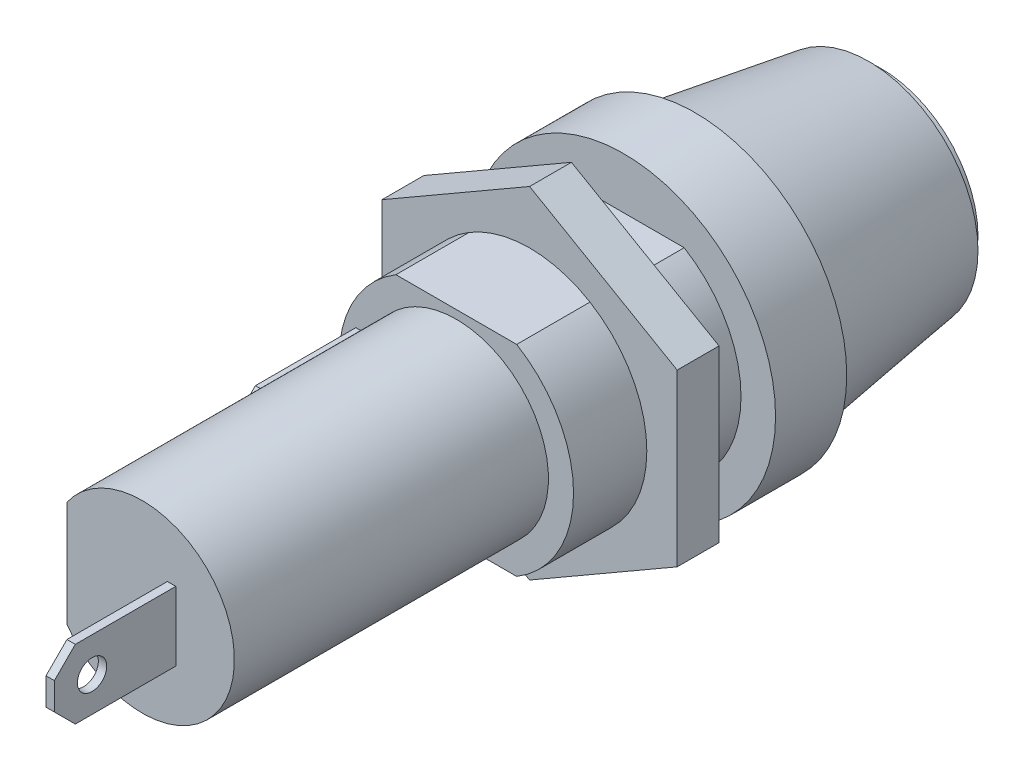
SolidWorks part; units mm, degrees
ref_plane "Front" through (0, 0, 0) normal (0, 0, 1) x (1, 0, 0)
ref_plane "Top" through (0, 0, 0) normal (0, 1, 0) x (1, 0, 0)
ref_plane "Right" through (0, 0, 0) normal (1, 0, 0) x (0, 0, -1)
sketch "Sketch1" plane through (0, 0, 0) normal (0, 0, 1) x (1, 0, 0)
  circle A0 centre (0, 0) radius 9.2075
  dimension "D1" = 18.415
extrude "Boss-Extrude1" add sketch "Sketch1" along normal blind 4.318
sketch "Sketch2" plane through (0, 0, 0) normal (1, 0, 0) x (0, 0, -1)
  line L0 (0, 0) -> (11.303, 0) construction
  line L1 (0, 0) -> (0, 8.4582)
  line L2 (0, -9.2075) -> (0, 9.2075) construction
  line L3 (0, 8.4582) -> (0.508, 8.4582)
  line L6 (10.541, 6.6294) -> (10.541, 5.8674)
  line L7 (10.541, 5.8674) -> (11.303, 5.8674)
  line L8 (11.303, 5.8674) -> (11.303, 0)
  line L9 (11.303, 0) -> (0, 0)
  line L10 (0.508, 8.4582) -> (0.6009, 8.143)
  line L11 (0.6009, 8.143) -> (10.541, 6.6294)
  dimension "D1" = 11.303
  dimension "D2" = 0.762
  dimension "D3" = 0.762
  dimension "D4" = 5.8674
  dimension "D5" = 0.508
  dimension "D6" = 8.4582
revolve "Revolve1" add sketch "Sketch2" angle 360 about L0
sketch "Sketch3" plane through (0, 0, 4.318) normal (0, 0, 1) x (1, 0, 0)
  circle A0 centre (0, 0) radius 7.112
  dimension "D1" = 14.224
extrude "Boss-Extrude2" add sketch "Sketch3" along normal blind 10.16
sketch "Sketch4" plane through (0, 0, 14.478) normal (0, 0, 1) x (1, 0, 0)
  circle A0 centre (0, 0) radius 5.588
  dimension "D1" = 11.176
extrude "Boss-Extrude3" add sketch "Sketch4" along normal blind 19.05
ref_plane "Plane1" through (0, 0, 7.493) normal (0, 0, 1) x (1, 0, 0)
sketch "Sketch6" plane through (0, 0, 0) normal (1, 0, 0) x (0, 0, -1)
  line L0 (-4.318, 7.112) -> (-4.318, -7.112) construction
  line L1 (-4.318, 6.096) -> (-14.478, 6.096)
  line L2 (-4.318, 6.096) -> (-4.318, 9.5721)
  line L3 (-4.318, 9.5721) -> (-14.478, 9.5721)
  line L4 (-14.478, 6.096) -> (-14.478, 9.5721)
  line L5 (-4.318, 0) -> (-14.478, 0) construction
  line L6 (-14.478, -6.096) -> (-4.318, -6.096)
  line L7 (-14.478, -6.096) -> (-14.478, -10.4456)
  line L8 (-14.478, -10.4456) -> (-4.318, -10.4456)
  line L9 (-4.318, -6.096) -> (-4.318, -10.4456)
  line L10 (-4.318, 9.2075) -> (-4.318, -9.2075) construction
  line L11 (-14.478, 5.588) -> (-14.478, -5.588) construction
  line L12 (-14.478, 7.112) -> (-14.478, -7.112) construction
  dimension "D1" = 12.192
  dimension "D2" = 6.096
extrude "Cut-Extrude1" cut sketch "Sketch6" against normal through all both and the other way through all
sketch "Sketch7" plane through (0, 0, 33.528) normal (0, 0, 1) x (1, 0, 0)
  line L0 (-7.112, 0) -> (0, 0) construction
  line L1 (-4.572, 5.08) -> (-7.112, 5.08)
  line L2 (-4.572, 5.08) -> (-4.572, -5.08)
  line L3 (-4.572, -5.08) -> (-7.112, -5.08)
  line L4 (-7.112, 5.08) -> (-7.112, -5.08)
  line L5 (-4.572, 0) -> (5.588, 0) construction
  circle A0 centre (0, 0) radius 5.588 construction
  dimension "D1" = 10.16
  dimension "D2" = 2.54
  dimension "D3" = 10.16
extrude "Cut-Extrude2" cut sketch "Sketch7" against normal up to surface (19.05 mm away) up to face at (0, 0, 14.478)
sketch "Sketch5" plane through (0, 0, 7.493) normal (0, 0, 1) x (1, 0, 0)
  line L1 (8.9535, 5.1693) -> (0, 10.3386)
  line L2 (0, 10.3386) -> (-8.9535, 5.1693)
  line L3 (-8.9535, 5.1693) -> (-8.9535, -5.1693)
  line L4 (-8.9535, -5.1693) -> (0, -10.3386)
  line L5 (0, -10.3386) -> (8.9535, -5.1693)
  line L6 (8.9535, -5.1693) -> (8.9535, 5.1693)
  circle A0 centre (0, 0) radius 8.9535 construction
  circle A1 centre (0, 0) radius 7.112
  dimension "D2" = 14.224
  dimension "D1" = 17.907
extrude "Boss-Extrude5" add sketch "Sketch5" along normal blind 2.54
sketch "Sketch8" plane through (0, 0, 33.528) normal (0, 0, 1) x (1, 0, 0)
  line L0 (-4.572, 0) -> (5.588, 0) construction
  line L1 (-4.572, -3.2129) -> (-4.572, 3.2129) construction
  line L3 (1.524, -2.0955) -> (2.032, -2.0955)
  line L4 (1.524, -2.0955) -> (1.524, 2.0955)
  line L5 (1.524, 2.0955) -> (2.032, 2.0955)
  line L6 (2.032, -2.0955) -> (2.032, 2.0955)
  line L7 (1.524, -2.0955) -> (2.032, 2.0955) construction
  line L8 (1.524, 2.0955) -> (2.032, -2.0955) construction
  arc A0 (-4.572, -3.2129) -> (-4.572, 3.2129) centre (0, 0) ccw construction
  point P7 (1.778, 0)
  dimension "D1" = 0.508
  dimension "D2" = 4.191
  dimension "D3" = 6.35
extrude "Boss-Extrude6" add sketch "Sketch8" along normal blind 7.366
sketch "Sketch9" plane through (0, 0, 14.478) normal (0, 0, 1) x (1, 0, 0)
  line L0 (-4.572, 0) -> (-7.112, 0) construction
  line L1 (-4.572, 3.2129) -> (-4.572, -3.2129) construction
  line L3 (-6.096, -2.0955) -> (-5.588, -2.0955)
  line L4 (-6.096, -2.0955) -> (-6.096, 2.0955)
  line L5 (-6.096, 2.0955) -> (-5.588, 2.0955)
  line L6 (-5.588, -2.0955) -> (-5.588, 2.0955)
  line L7 (-6.096, -2.0955) -> (-5.588, 2.0955) construction
  line L8 (-6.096, 2.0955) -> (-5.588, -2.0955) construction
  arc A0 (-3.6632, 6.096) -> (-3.6632, -6.096) centre (0, 0) ccw construction
  point P7 (-5.842, 0)
  point P15 (-5.842, 0)
  dimension "D1" = 0.508
  dimension "D2" = 4.191
extrude "Boss-Extrude7" add sketch "Sketch9" along normal blind 7.366
sketch "Sketch10" plane through (1.524, 0, 0) normal (-1, 0, 0) x (0, 0, 1)
  line B0 (40.894, 0) -> (33.528, 0) construction
  line B1 (38.608, 2.0955) -> (38.608, -2.0955) construction
  line B2 (39.624, 2.0955) -> (40.894, 0.8255)
  line B3 (40.894, 0.8255) -> (40.894, 2.0955)
  line B4 (40.894, 2.0955) -> (39.624, 2.0955)
  line B5 (39.624, -2.0955) -> (40.894, -0.8255)
  line B6 (40.894, -0.8255) -> (40.894, -2.0955)
  line B7 (40.894, -2.0955) -> (39.624, -2.0955)
  line B8 (33.528, 2.0955) -> (40.894, 2.0955) construction
  line B9 (33.528, 2.0955) -> (33.528, -2.0955) construction
  line B10 (33.528, -2.0955) -> (40.894, -2.0955) construction
  line B11 (40.894, 2.0955) -> (40.894, -2.0955) construction
  circle B12 centre (38.608, 0) radius 0.889
sketch_block_instance "Block1-1"
sketch_block "Block1" parameters "D2"=1.778, "D1"=2.286, "D3"=1.27, "D4"=1.27, "D5"=1.27, "D6"=1.27, "D7"=4.191, "D8"=7.366
extrude "Cut-Extrude3" cut sketch "Sketch10" against normal up to surface (0.508 mm away) up to face at (2.032, 0, 37.211)
sketch "Sketch11" plane through (-6.096, 0, 0) normal (-1, 0, 0) x (0, 0, 1)
  line B0 (20.574, 2.0955) -> (21.844, 0.8255)
  line B1 (21.844, 0.8255) -> (21.844, 2.0955)
  line B2 (21.844, 2.0955) -> (20.574, 2.0955)
  line B3 (20.574, -2.0955) -> (21.844, -0.8255)
  line B4 (21.844, -0.8255) -> (21.844, -2.0955)
  line B5 (21.844, -2.0955) -> (20.574, -2.0955)
  line B6 (21.844, 2.0955) -> (21.844, -2.0955) construction
  circle B7 centre (19.558, 0) radius 0.889
sketch_block_instance "Block1-2"
extrude "Cut-Extrude4" cut sketch "Sketch11" against normal up to surface (0.508 mm away) up to face at (-5.588, 0, 18.161)
sketch "Sketch12" plane through (0, 0, -11.303) normal (0, 0, -1) x (-1, 0, 0)
  text T1 "FUSE" font "Century Gothic" height 3.175
extrude "Cut-Extrude5" cut sketch "Sketch12" against normal blind 0.254
equation "\"D2@Sketch6\"=\"D1@Sketch6\"/2"
